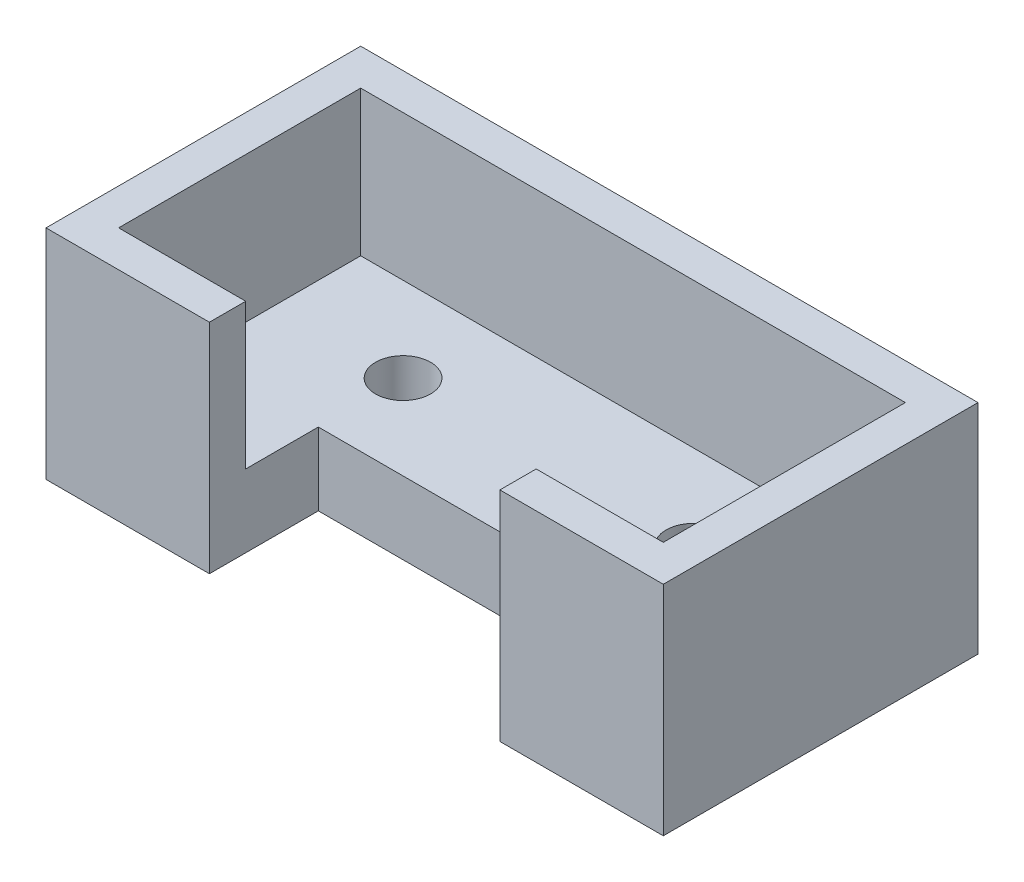
SolidWorks part; units mm, degrees
ref_plane "Front Plane" through (0, 0, 0) normal (0, 0, 1) x (1, 0, 0)
ref_plane "Top Plane" through (0, 0, 0) normal (0, 1, 0) x (1, 0, 0)
ref_plane "Right Plane" through (0, 0, 0) normal (1, 0, 0) x (0, 0, -1)
ref_plane "Plane1" through (0, 0, 0) normal (0, -1, 0) x (-1, 0, 0)
ref_plane "Plane2" through (0, 0, 0) normal (0, -1, 0) x (-1, 0, 0)
sketch "Sketch10" plane through (25.3958, 0, 0) normal (1, 0, 0) x (0, 0, -1)
  line L0 (2.5694, 8.7) -> (2.5694, -3.3) construction
  line L1 (12.5694, -3.3) -> (15.5694, -3.3)
  line L2 (12.5694, -3.3) -> (-7.4306, -3.3)
  line L3 (15.5694, -3.3) -> (15.5694, 8.7)
  line L5 (-7.4306, 8.7) -> (12.5694, 8.7)
  line L7 (15.5694, 8.7) -> (12.5694, 8.7)
  line L8 (-7.4306, -3.3) -> (-10.4306, -3.3)
  line L9 (-10.4306, -3.3) -> (-10.4306, 8.7)
  line L10 (-10.4306, 8.7) -> (-7.4306, 8.7)
  dimension "D1" = 12
  dimension "D2" = 3
  dimension "D3" = 3
  dimension "D4" = 10
  dimension "D5" = 26
extrude "Boss-Extrude10" add sketch "Sketch10" along normal blind 3
sketch "Sketch12" plane through (25.3958, 0, 0) normal (-1, 0, 0) x (0, 0, 1)
  line L0 (-15.5694, 8.7) -> (-15.5694, -3.3)
  line L1 (-15.5694, -3.3) -> (-12.5694, -3.3)
  line L2 (-12.5694, -3.3) -> (-12.5694, 8.7)
  line L3 (-15.5694, 8.7) -> (10.4306, 8.7) construction
  line L4 (-12.5694, 8.7) -> (-15.5694, 8.7)
  line L5 (-15.5694, 8.7) -> (10.4306, 8.7) construction
  line L6 (-2.5694, 8.7) -> (-2.5694, 0) construction
  line L7 (7.4306, 0) -> (-12.5694, 0) construction
  line L8 (7.4306, 8.7) -> (10.4306, 8.7)
  line L9 (7.4306, -3.3) -> (7.4306, 8.7)
  line L10 (10.4306, -3.3) -> (7.4306, -3.3)
  line L11 (10.4306, 8.7) -> (10.4306, -3.3)
extrude "Boss-Extrude11" add sketch "Sketch12" along normal blind 48
sketch "Sketch13" plane through (0, 0, -12.5694) normal (0, 0, 1) x (1, 0, 0)
  line L0 (-22.6042, -3.3) -> (-22.6042, 8.7)
  line L1 (-22.6042, -3.3) -> (-19.6042, -3.3)
  line L2 (-19.6042, -3.3) -> (-19.6042, 8.7)
  line L3 (-22.6042, 8.7) -> (25.3958, 8.7) construction
  line L4 (-19.6042, 8.7) -> (-22.6042, 8.7)
extrude "Boss-Extrude12" add sketch "Sketch13" along normal up to next
sketch "Sketch14" plane through (0, 0, 10.4306) normal (0, 0, 1) x (1, 0, 0)
  line L0 (2.8958, -3.3) -> (2.8958, 8.7) construction
  line L1 (-2.1042, -3.3) -> (7.8958, -3.3) construction
  line L2 (28.3958, 8.7) -> (-22.6042, 8.7) construction
  line L3 (2.8958, 8.7) -> (14.8958, 8.7) construction
  line L4 (2.8958, 8.7) -> (14.8958, 8.7)
  line L5 (14.8958, 8.7) -> (14.8958, -3.3)
  line L6 (28.3958, -3.3) -> (-22.6042, -3.3) construction
  line L7 (14.8958, -3.3) -> (-9.1042, -3.3)
  line L8 (-22.6042, -3.3) -> (28.3958, -3.3) construction
  line L9 (-9.1042, -3.3) -> (-9.1042, 8.7)
  line L10 (-9.1042, 8.7) -> (2.8958, 8.7)
  dimension "D1" = 12
  dimension "D2" = 12
extrude "Cut-Extrude1" cut sketch "Sketch14" against normal blind 3
sketch "Sketch15" plane through (0, -3.3, 0) normal (0, -1, 0) x (1, 0, 0)
  line L0 (-22.6042, -15.5694) -> (-22.6042, 10.4306)
  line L1 (-22.6042, 10.4306) -> (-9.1042, 10.4306)
  line L2 (-9.1042, 10.4306) -> (-9.1042, 7.4306)
  line L3 (-9.1042, 7.4306) -> (-9.1042, 1.4306)
  line L4 (-9.1042, 1.4306) -> (14.8958, 1.4306)
  line L5 (14.8958, 1.4306) -> (14.8958, 7.4306)
  line L6 (14.8958, 7.4306) -> (14.8958, 10.4306)
  line L7 (14.8958, 10.4306) -> (28.3958, 10.4306)
  line L8 (28.3958, 10.4306) -> (28.3958, -15.5694)
  line L9 (28.3958, -15.5694) -> (-22.6042, -15.5694)
  line L10 (-22.6042, -15.5694) -> (-22.7513, -15.6867)
  dimension "D1" = 9
  dimension "D2" = 24
extrude "Boss-Extrude13" add sketch "Sketch15" along normal blind 6
sketch "Sketch16" plane through (0, -3.3, 0) normal (0, 1, 0) x (1, 0, 0)
  line L0 (-9.1042, -1.4306) -> (-9.1042, 12.5694) construction
  line L1 (-19.6042, 12.5694) -> (25.3958, 12.5694) construction
  line L2 (-9.1042, 12.5694) -> (14.8958, 12.5694) construction
  line L3 (14.8958, 12.5694) -> (14.8958, -1.4306) construction
  line L4 (14.8958, 5.5694) -> (-9.1042, 5.5694) construction
  circle A0 centre (-9.1042, 5.5694) radius 2.2733
  circle A1 centre (14.8958, 5.5694) radius 2.2733
  dimension "D5" = 4.5466
  dimension "D6" = 4.5466
  dimension "D1" = 0
  dimension "D2" = 0
  dimension "D3" = 0
  dimension "D4" = 0
extrude "Cut-Extrude2" cut sketch "Sketch16" against normal up to next
